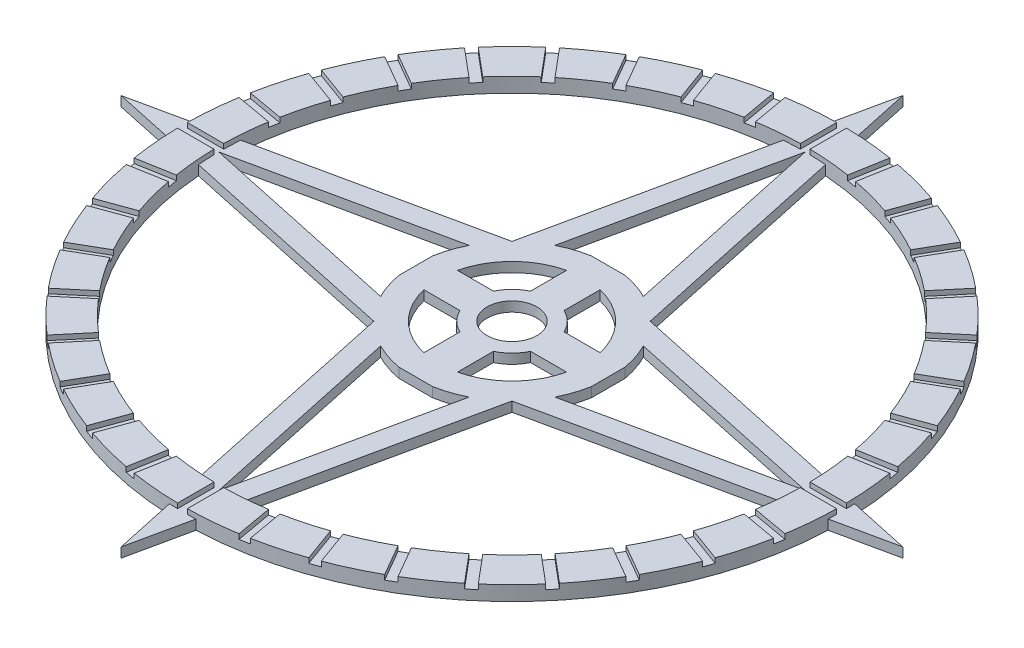
SolidWorks part; units mm, degrees
ref_plane "Front Plane" through (0, 0, 0) normal (0, 0, 1) x (1, 0, 0)
ref_plane "Top Plane" through (0, 0, 0) normal (0, 1, 0) x (1, 0, 0)
ref_plane "Right Plane" through (0, 0, 0) normal (1, 0, 0) x (0, 0, -1)
sketch "Sketch1" plane through (0, 0, 0) normal (0, 1, 0) x (1, 0, 0)
  line L0 (0, 0) -> (0, 80)
  line L1 (0, 0) -> (14.1421, 14.1421)
  line L2 (0, 0) -> (0, 60)
  line L3 (0, 80) -> (14.1421, 14.1421)
  line L4 (0, 60) -> (10.6066, 10.6066)
  line L5 (0, 0) -> (-14.1421, 14.1421)
  line L6 (0, 60) -> (-10.6066, 10.6066)
  line L7 (0, 80) -> (-14.1421, 14.1421)
  line L8 (80, 0) -> (14.1421, -14.1421)
  line L9 (60, 0) -> (10.6066, -10.6066)
  line L10 (60, 0) -> (10.6066, 10.6066)
  line L11 (80, 0) -> (14.1421, 14.1421)
  line L12 (0, 0) -> (14.1421, -14.1421)
  line L13 (0, -80) -> (-14.1421, -14.1421)
  line L14 (0, -60) -> (-10.6066, -10.6066)
  line L15 (0, -60) -> (10.6066, -10.6066)
  line L16 (0, -80) -> (14.1421, -14.1421)
  line L17 (0, 0) -> (-14.1421, -14.1421)
  line L18 (-80, 0) -> (-14.1421, 14.1421)
  line L19 (-60, 0) -> (-10.6066, 10.6066)
  line L20 (-60, 0) -> (-10.6066, -10.6066)
  line L21 (-80, 0) -> (-14.1421, -14.1421)
  line L22 (0, 0) -> (-14.1421, 14.1421)
  line L23 (-19.7027, -3.4357) -> (19.7027, -3.4357)
  line L24 (3.4357, -19.7027) -> (-3.4357, -19.7027)
  line L25 (3.4357, -19.7027) -> (3.4357, 19.7027)
  line L26 (3.4357, 19.7027) -> (-3.4357, 19.7027)
  line L27 (-3.4357, -19.7027) -> (-3.4357, 19.7027)
  line L28 (3.4357, -19.7027) -> (-3.4357, 19.7027) construction
  line L29 (3.4357, 19.7027) -> (-3.4357, -19.7027) construction
  line L30 (-19.7027, -3.4357) -> (19.7027, 3.4357) construction
  line L31 (19.7027, -3.4357) -> (-19.7027, 3.4357) construction
  line L32 (-19.7027, 3.4357) -> (19.7027, 3.4357)
  line L33 (-19.7027, -3.4357) -> (-19.7027, 3.4357)
  line L34 (19.7027, -3.4357) -> (19.7027, 3.4357)
  line L35 (-3.4357, 19.7027) -> (-3.4357, -19.7027)
  line L36 (-3.4357, 19.7027) -> (3.4357, -19.7027) construction
  line L37 (-3.4357, -19.7027) -> (3.4357, 19.7027) construction
  line L38 (3.4357, 19.7027) -> (3.4357, -19.7027)
  line L39 (-3.4357, 19.7027) -> (3.4357, 19.7027)
  line L40 (-3.4357, -19.7027) -> (3.4357, -19.7027)
  line L41 (19.7027, 3.4357) -> (-19.7027, 3.4357)
  line L42 (19.7027, 3.4357) -> (-19.7027, -3.4357) construction
  line L43 (-19.7027, 3.4357) -> (19.7027, -3.4357) construction
  line L44 (19.7027, -3.4357) -> (-19.7027, -3.4357)
  line L45 (19.7027, 3.4357) -> (19.7027, -3.4357)
  line L46 (-19.7027, 3.4357) -> (-19.7027, -3.4357)
  circle A0 centre (0, 0) radius 5.1
  circle A1 centre (0, 0) radius 8
  circle A2 centre (0, 0) radius 20
  circle A3 centre (0, 0) radius 15
  point P33 (0, 0)
  point P50 (0, 0)
  dimension "D1" = 16
  dimension "D2" = 10.2
  dimension "D4" = 40
  dimension "D3" = 80
  dimension "D5" = 45
  dimension "D6" = 60
  dimension "D7" = 4
  dimension "D8" = 4
extrude "Boss-Extrude1" add sketch "Sketch1" along normal blind 2
sketch "Sketch3" plane through (0, 2, 0) normal (0, 1, 0) x (1, 0, 0)
  circle A0 centre (0, 0) radius 60
  circle A1 centre (0, 0) radius 67.4541
extrude "Boss-Extrude3" add sketch "Sketch3" along normal blind 3 from offset 2 offset against normal yes
sketch "Sketch4" plane through (0, 3, 0) normal (0, 1, 0) x (1, 0, 0)
  line L0 (0, 0) -> (0, 60)
  line L1 (0, 0) -> (10.4189, 59.0885)
  line L2 (1, 59) -> (-1, 59)
  line L3 (1, 59) -> (1, 69)
  line L4 (1, 69) -> (-1, 69)
  line L5 (-1, 59) -> (-1, 69)
  line L6 (1, 59) -> (-1, 69) construction
  line L7 (1, 69) -> (-1, 59) construction
  line L8 (11.2301, 57.93) -> (12.9665, 67.7781)
  line L9 (11.2301, 57.93) -> (10.9969, 68.1254) construction
  line L10 (12.9665, 67.7781) -> (9.2604, 58.2773) construction
  line L11 (9.2604, 58.2773) -> (10.9969, 68.1254)
  line L12 (11.2301, 57.93) -> (9.2604, 58.2773)
  line L13 (12.9665, 67.7781) -> (10.9969, 68.1254)
  line L14 (0, 0) -> (20.5212, 56.3816)
  line L15 (21.1189, 55.0998) -> (24.5391, 64.4968)
  line L16 (21.1189, 55.0998) -> (22.6597, 65.1808) construction
  line L17 (24.5391, 64.4968) -> (19.2395, 55.7839) construction
  line L18 (19.2395, 55.7839) -> (22.6597, 65.1808)
  line L19 (21.1189, 55.0998) -> (19.2395, 55.7839)
  line L20 (24.5391, 64.4968) -> (22.6597, 65.1808)
  line L21 (0, 0) -> (30, 51.9615)
  line L22 (30.366, 50.5955) -> (35.366, 59.2558)
  line L23 (30.366, 50.5955) -> (33.634, 60.2558) construction
  line L24 (35.366, 59.2558) -> (28.634, 51.5955) construction
  line L25 (28.634, 51.5955) -> (33.634, 60.2558)
  line L26 (30.366, 50.5955) -> (28.634, 51.5955)
  line L27 (35.366, 59.2558) -> (33.634, 60.2558)
  line L28 (0, 0) -> (38.5673, 45.9627)
  line L29 (38.6905, 44.5538) -> (45.1184, 52.2143)
  line L30 (38.6905, 44.5538) -> (43.5863, 53.4999) construction
  line L31 (45.1184, 52.2143) -> (37.1584, 45.8394) construction
  line L32 (37.1584, 45.8394) -> (43.5863, 53.4999)
  line L33 (38.6905, 44.5538) -> (37.1584, 45.8394)
  line L34 (45.1184, 52.2143) -> (43.5863, 53.4999)
  line L35 (0, 0) -> (45.9627, 38.5673)
  line L36 (45.8394, 37.1584) -> (53.4999, 43.5863)
  line L37 (45.8394, 37.1584) -> (52.2143, 45.1184) construction
  line L38 (53.4999, 43.5863) -> (44.5538, 38.6905) construction
  line L39 (44.5538, 38.6905) -> (52.2143, 45.1184)
  line L40 (45.8394, 37.1584) -> (44.5538, 38.6905)
  line L41 (53.4999, 43.5863) -> (52.2143, 45.1184)
  line L42 (0, 0) -> (51.9615, 30)
  line L43 (51.5955, 28.634) -> (60.2558, 33.634)
  line L44 (51.5955, 28.634) -> (59.2558, 35.366) construction
  line L45 (60.2558, 33.634) -> (50.5955, 30.366) construction
  line L46 (50.5955, 30.366) -> (59.2558, 35.366)
  line L47 (51.5955, 28.634) -> (50.5955, 30.366)
  line L48 (60.2558, 33.634) -> (59.2558, 35.366)
  line L49 (0, 0) -> (56.3816, 20.5212)
  line L50 (55.7839, 19.2395) -> (65.1808, 22.6597)
  line L51 (55.7839, 19.2395) -> (64.4968, 24.5391) construction
  line L52 (65.1808, 22.6597) -> (55.0998, 21.1189) construction
  line L53 (55.0998, 21.1189) -> (64.4968, 24.5391)
  line L54 (55.7839, 19.2395) -> (55.0998, 21.1189)
  line L55 (65.1808, 22.6597) -> (64.4968, 24.5391)
  line L56 (0, 0) -> (59.0885, 10.4189)
  line L57 (58.2773, 9.2604) -> (68.1254, 10.9969)
  line L58 (58.2773, 9.2604) -> (67.7781, 12.9665) construction
  line L59 (68.1254, 10.9969) -> (57.93, 11.2301) construction
  line L60 (57.93, 11.2301) -> (67.7781, 12.9665)
  line L61 (58.2773, 9.2604) -> (57.93, 11.2301)
  line L62 (68.1254, 10.9969) -> (67.7781, 12.9665)
  line L63 (0, 0) -> (60, 0)
  line L64 (59, -1) -> (69, -1)
  line L65 (59, -1) -> (69, 1) construction
  line L66 (69, -1) -> (59, 1) construction
  line L67 (59, 1) -> (69, 1)
  line L68 (59, -1) -> (59, 1)
  line L69 (69, -1) -> (69, 1)
  line L70 (0, 0) -> (59.0885, -10.4189)
  line L71 (57.93, -11.2301) -> (67.7781, -12.9665)
  line L72 (57.93, -11.2301) -> (68.1254, -10.9969) construction
  line L73 (67.7781, -12.9665) -> (58.2773, -9.2604) construction
  line L74 (58.2773, -9.2604) -> (68.1254, -10.9969)
  line L75 (57.93, -11.2301) -> (58.2773, -9.2604)
  line L76 (67.7781, -12.9665) -> (68.1254, -10.9969)
  line L77 (0, 0) -> (56.3816, -20.5212)
  line L78 (55.0998, -21.1189) -> (64.4968, -24.5391)
  line L79 (55.0998, -21.1189) -> (65.1808, -22.6597) construction
  line L80 (64.4968, -24.5391) -> (55.7839, -19.2395) construction
  line L81 (55.7839, -19.2395) -> (65.1808, -22.6597)
  line L82 (55.0998, -21.1189) -> (55.7839, -19.2395)
  line L83 (64.4968, -24.5391) -> (65.1808, -22.6597)
  line L84 (0, 0) -> (51.9615, -30)
  line L85 (50.5955, -30.366) -> (59.2558, -35.366)
  line L86 (50.5955, -30.366) -> (60.2558, -33.634) construction
  line L87 (59.2558, -35.366) -> (51.5955, -28.634) construction
  line L88 (51.5955, -28.634) -> (60.2558, -33.634)
  line L89 (50.5955, -30.366) -> (51.5955, -28.634)
  line L90 (59.2558, -35.366) -> (60.2558, -33.634)
  line L91 (0, 0) -> (45.9627, -38.5673)
  line L92 (44.5538, -38.6905) -> (52.2143, -45.1184)
  line L93 (44.5538, -38.6905) -> (53.4999, -43.5863) construction
  line L94 (52.2143, -45.1184) -> (45.8394, -37.1584) construction
  line L95 (45.8394, -37.1584) -> (53.4999, -43.5863)
  line L96 (44.5538, -38.6905) -> (45.8394, -37.1584)
  line L97 (52.2143, -45.1184) -> (53.4999, -43.5863)
  line L98 (0, 0) -> (38.5673, -45.9627)
  line L99 (37.1584, -45.8394) -> (43.5863, -53.4999)
  line L100 (37.1584, -45.8394) -> (45.1184, -52.2143) construction
  line L101 (43.5863, -53.4999) -> (38.6905, -44.5538) construction
  line L102 (38.6905, -44.5538) -> (45.1184, -52.2143)
  line L103 (37.1584, -45.8394) -> (38.6905, -44.5538)
  line L104 (43.5863, -53.4999) -> (45.1184, -52.2143)
  line L105 (0, 0) -> (30, -51.9615)
  line L106 (28.634, -51.5955) -> (33.634, -60.2558)
  line L107 (28.634, -51.5955) -> (35.366, -59.2558) construction
  line L108 (33.634, -60.2558) -> (30.366, -50.5955) construction
  line L109 (30.366, -50.5955) -> (35.366, -59.2558)
  line L110 (28.634, -51.5955) -> (30.366, -50.5955)
  line L111 (33.634, -60.2558) -> (35.366, -59.2558)
  line L112 (0, 0) -> (20.5212, -56.3816)
  line L113 (19.2395, -55.7839) -> (22.6597, -65.1808)
  line L114 (19.2395, -55.7839) -> (24.5391, -64.4968) construction
  line L115 (22.6597, -65.1808) -> (21.1189, -55.0998) construction
  line L116 (21.1189, -55.0998) -> (24.5391, -64.4968)
  line L117 (19.2395, -55.7839) -> (21.1189, -55.0998)
  line L118 (22.6597, -65.1808) -> (24.5391, -64.4968)
  line L119 (0, 0) -> (10.4189, -59.0885)
  line L120 (9.2604, -58.2773) -> (10.9969, -68.1254)
  line L121 (9.2604, -58.2773) -> (12.9665, -67.7781) construction
  line L122 (10.9969, -68.1254) -> (11.2301, -57.93) construction
  line L123 (11.2301, -57.93) -> (12.9665, -67.7781)
  line L124 (9.2604, -58.2773) -> (11.2301, -57.93)
  line L125 (10.9969, -68.1254) -> (12.9665, -67.7781)
  line L126 (0, 0) -> (0, -60)
  line L127 (-1, -59) -> (-1, -69)
  line L128 (-1, -59) -> (1, -69) construction
  line L129 (-1, -69) -> (1, -59) construction
  line L130 (1, -59) -> (1, -69)
  line L131 (-1, -59) -> (1, -59)
  line L132 (-1, -69) -> (1, -69)
  line L133 (0, 0) -> (-10.4189, -59.0885)
  line L134 (-11.2301, -57.93) -> (-12.9665, -67.7781)
  line L135 (-11.2301, -57.93) -> (-10.9969, -68.1254) construction
  line L136 (-12.9665, -67.7781) -> (-9.2604, -58.2773) construction
  line L137 (-9.2604, -58.2773) -> (-10.9969, -68.1254)
  line L138 (-11.2301, -57.93) -> (-9.2604, -58.2773)
  line L139 (-12.9665, -67.7781) -> (-10.9969, -68.1254)
  line L140 (0, 0) -> (-20.5212, -56.3816)
  line L141 (-21.1189, -55.0998) -> (-24.5391, -64.4968)
  line L142 (-21.1189, -55.0998) -> (-22.6597, -65.1808) construction
  line L143 (-24.5391, -64.4968) -> (-19.2395, -55.7839) construction
  line L144 (-19.2395, -55.7839) -> (-22.6597, -65.1808)
  line L145 (-21.1189, -55.0998) -> (-19.2395, -55.7839)
  line L146 (-24.5391, -64.4968) -> (-22.6597, -65.1808)
  line L147 (0, 0) -> (-30, -51.9615)
  line L148 (-30.366, -50.5955) -> (-35.366, -59.2558)
  line L149 (-30.366, -50.5955) -> (-33.634, -60.2558) construction
  line L150 (-35.366, -59.2558) -> (-28.634, -51.5955) construction
  line L151 (-28.634, -51.5955) -> (-33.634, -60.2558)
  line L152 (-30.366, -50.5955) -> (-28.634, -51.5955)
  line L153 (-35.366, -59.2558) -> (-33.634, -60.2558)
  line L154 (0, 0) -> (-38.5673, -45.9627)
  line L155 (-38.6905, -44.5538) -> (-45.1184, -52.2143)
  line L156 (-38.6905, -44.5538) -> (-43.5863, -53.4999) construction
  line L157 (-45.1184, -52.2143) -> (-37.1584, -45.8394) construction
  line L158 (-37.1584, -45.8394) -> (-43.5863, -53.4999)
  line L159 (-38.6905, -44.5538) -> (-37.1584, -45.8394)
  line L160 (-45.1184, -52.2143) -> (-43.5863, -53.4999)
  line L161 (0, 0) -> (-45.9627, -38.5673)
  line L162 (-45.8394, -37.1584) -> (-53.4999, -43.5863)
  line L163 (-45.8394, -37.1584) -> (-52.2143, -45.1184) construction
  line L164 (-53.4999, -43.5863) -> (-44.5538, -38.6905) construction
  line L165 (-44.5538, -38.6905) -> (-52.2143, -45.1184)
  line L166 (-45.8394, -37.1584) -> (-44.5538, -38.6905)
  line L167 (-53.4999, -43.5863) -> (-52.2143, -45.1184)
  line L168 (0, 0) -> (-51.9615, -30)
  line L169 (-51.5955, -28.634) -> (-60.2558, -33.634)
  line L170 (-51.5955, -28.634) -> (-59.2558, -35.366) construction
  line L171 (-60.2558, -33.634) -> (-50.5955, -30.366) construction
  line L172 (-50.5955, -30.366) -> (-59.2558, -35.366)
  line L173 (-51.5955, -28.634) -> (-50.5955, -30.366)
  line L174 (-60.2558, -33.634) -> (-59.2558, -35.366)
  line L175 (0, 0) -> (-56.3816, -20.5212)
  line L176 (-55.7839, -19.2395) -> (-65.1808, -22.6597)
  line L177 (-55.7839, -19.2395) -> (-64.4968, -24.5391) construction
  line L178 (-65.1808, -22.6597) -> (-55.0998, -21.1189) construction
  line L179 (-55.0998, -21.1189) -> (-64.4968, -24.5391)
  line L180 (-55.7839, -19.2395) -> (-55.0998, -21.1189)
  line L181 (-65.1808, -22.6597) -> (-64.4968, -24.5391)
  line L182 (0, 0) -> (-59.0885, -10.4189)
  line L183 (-58.2773, -9.2604) -> (-68.1254, -10.9969)
  line L184 (-58.2773, -9.2604) -> (-67.7781, -12.9665) construction
  line L185 (-68.1254, -10.9969) -> (-57.93, -11.2301) construction
  line L186 (-57.93, -11.2301) -> (-67.7781, -12.9665)
  line L187 (-58.2773, -9.2604) -> (-57.93, -11.2301)
  line L188 (-68.1254, -10.9969) -> (-67.7781, -12.9665)
  line L189 (0, 0) -> (-60, 0)
  line L190 (-59, 1) -> (-69, 1)
  line L191 (-59, 1) -> (-69, -1) construction
  line L192 (-69, 1) -> (-59, -1) construction
  line L193 (-59, -1) -> (-69, -1)
  line L194 (-59, 1) -> (-59, -1)
  line L195 (-69, 1) -> (-69, -1)
  line L196 (0, 0) -> (-59.0885, 10.4189)
  line L197 (-57.93, 11.2301) -> (-67.7781, 12.9665)
  line L198 (-57.93, 11.2301) -> (-68.1254, 10.9969) construction
  line L199 (-67.7781, 12.9665) -> (-58.2773, 9.2604) construction
  line L200 (-58.2773, 9.2604) -> (-68.1254, 10.9969)
  line L201 (-57.93, 11.2301) -> (-58.2773, 9.2604)
  line L202 (-67.7781, 12.9665) -> (-68.1254, 10.9969)
  line L203 (0, 0) -> (-56.3816, 20.5212)
  line L204 (-55.0998, 21.1189) -> (-64.4968, 24.5391)
  line L205 (-55.0998, 21.1189) -> (-65.1808, 22.6597) construction
  line L206 (-64.4968, 24.5391) -> (-55.7839, 19.2395) construction
  line L207 (-55.7839, 19.2395) -> (-65.1808, 22.6597)
  line L208 (-55.0998, 21.1189) -> (-55.7839, 19.2395)
  line L209 (-64.4968, 24.5391) -> (-65.1808, 22.6597)
  line L210 (0, 0) -> (-51.9615, 30)
  line L211 (-50.5955, 30.366) -> (-59.2558, 35.366)
  line L212 (-50.5955, 30.366) -> (-60.2558, 33.634) construction
  line L213 (-59.2558, 35.366) -> (-51.5955, 28.634) construction
  line L214 (-51.5955, 28.634) -> (-60.2558, 33.634)
  line L215 (-50.5955, 30.366) -> (-51.5955, 28.634)
  line L216 (-59.2558, 35.366) -> (-60.2558, 33.634)
  line L217 (0, 0) -> (-45.9627, 38.5673)
  line L218 (-44.5538, 38.6905) -> (-52.2143, 45.1184)
  line L219 (-44.5538, 38.6905) -> (-53.4999, 43.5863) construction
  line L220 (-52.2143, 45.1184) -> (-45.8394, 37.1584) construction
  line L221 (-45.8394, 37.1584) -> (-53.4999, 43.5863)
  line L222 (-44.5538, 38.6905) -> (-45.8394, 37.1584)
  line L223 (-52.2143, 45.1184) -> (-53.4999, 43.5863)
  line L224 (0, 0) -> (-38.5673, 45.9627)
  line L225 (-37.1584, 45.8394) -> (-43.5863, 53.4999)
  line L226 (-37.1584, 45.8394) -> (-45.1184, 52.2143) construction
  line L227 (-43.5863, 53.4999) -> (-38.6905, 44.5538) construction
  line L228 (-38.6905, 44.5538) -> (-45.1184, 52.2143)
  line L229 (-37.1584, 45.8394) -> (-38.6905, 44.5538)
  line L230 (-43.5863, 53.4999) -> (-45.1184, 52.2143)
  line L231 (0, 0) -> (-30, 51.9615)
  line L232 (-28.634, 51.5955) -> (-33.634, 60.2558)
  line L233 (-28.634, 51.5955) -> (-35.366, 59.2558) construction
  line L234 (-33.634, 60.2558) -> (-30.366, 50.5955) construction
  line L235 (-30.366, 50.5955) -> (-35.366, 59.2558)
  line L236 (-28.634, 51.5955) -> (-30.366, 50.5955)
  line L237 (-33.634, 60.2558) -> (-35.366, 59.2558)
  line L238 (0, 0) -> (-20.5212, 56.3816)
  line L239 (-19.2395, 55.7839) -> (-22.6597, 65.1808)
  line L240 (-19.2395, 55.7839) -> (-24.5391, 64.4968) construction
  line L241 (-22.6597, 65.1808) -> (-21.1189, 55.0998) construction
  line L242 (-21.1189, 55.0998) -> (-24.5391, 64.4968)
  line L243 (-19.2395, 55.7839) -> (-21.1189, 55.0998)
  line L244 (-22.6597, 65.1808) -> (-24.5391, 64.4968)
  line L245 (0, 0) -> (-10.4189, 59.0885)
  line L246 (-9.2604, 58.2773) -> (-10.9969, 68.1254)
  line L247 (-9.2604, 58.2773) -> (-12.9665, 67.7781) construction
  line L248 (-10.9969, 68.1254) -> (-11.2301, 57.93) construction
  line L249 (-11.2301, 57.93) -> (-12.9665, 67.7781)
  line L250 (-9.2604, 58.2773) -> (-11.2301, 57.93)
  line L251 (-10.9969, 68.1254) -> (-12.9665, 67.7781)
  point P4 (0, 64)
  point P187 (0, 0)
  circle M4 centre (0, 0) radius 67.4541
  circle M5 centre (0, 0) radius 60
  dimension "D1" = 10
  dimension "D2" = 2
  dimension "D3" = 4
  dimension "D4" = 36
extrude "Cut-Extrude2" cut sketch "Sketch4" against normal blind 1 contours L5 L3 M5 M4 | L11 L8 M5 M4 | L18 L15 M5 M4 | L25 L22 M5 M4 | L32 L29 M5 M4 | L39 L36 M5 M4 | L46 L43 M5 M4 | L53 L50 M5 M4 | L60 L57 M5 M4 | L67 L64 M5 M4 | L74 L71 M5 M4 | L81 L78 M5 M4 | L88 L85 M5 M4 | L95 L92 M5 M4 | L102 L99 M5 M4 | L109 L106 M5 M4 | L116 L113 M5 M4 | L123 L120 M5 M4 | L130 L127 M5 M4 | L137 L134 M5 M4 | L144 L141 M5 M4 | L151 L148 M5 M4 | L158 L155 M5 M4 | L165 L162 M5 M4 | L172 L169 M5 M4 | L179 L176 M5 M4 | L186 L183 M5 M4 | L193 L190 M5 M4 | L200 L197 M5 M4 | L207 L204 M5 M4 | L214 L211 M5 M4 | L221 L218 M5 M4 | L228 L225 M5 M4 | L235 L232 M5 M4 | L242 L239 M5 M4 | L249 L246 M5 M4
